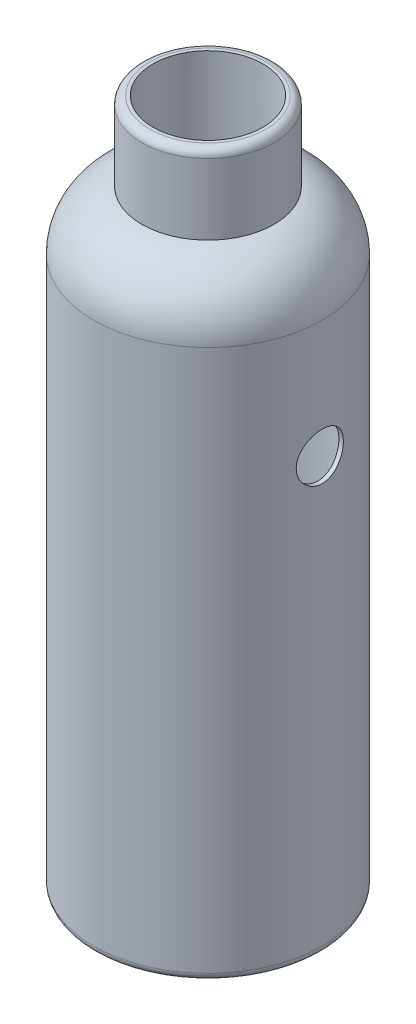
SolidWorks part; units mm, degrees
material "1060 Alloy"
ref_plane "Front Plane" through (0, 0, 0) normal (0, 0, 1) x (1, 0, 0)
ref_plane "Top Plane" through (0, 0, 0) normal (0, 1, 0) x (1, 0, 0)
ref_plane "Right Plane" through (0, 0, 0) normal (1, 0, 0) x (0, 0, -1)
sketch "Sketch1" plane through (0, 0, 0) normal (0, 1, 0) x (1, 0, 0)
  circle A0 centre (0, 0) radius 36.9633
  dimension "D1" = 73.9267
extrude "Boss-Extrude1" add sketch "Sketch1" along normal blind 171.45
fillet "Fillet1" radius 2.54 1 edges at (0, 0, 36.9633)
ref_plane "Plane1" through (0, 196.85, 0) normal (0, 1, 0) x (1, 0, 0)
sketch "Sketch2" plane through (0, 196.85, 0) normal (0, 1, 0) x (1, 0, 0)
  circle A0 centre (0, 0) radius 20.6883
  dimension "D1" = 41.3766
sketch "Sketch10" plane through (0, 171.45, 0) normal (0, 1, 0) x (1, 0, 0)
  circle A0 centre (0, 0) radius 36.9633
  dimension "D1" = 73.9267
extrude "Boss-Extrude2" add sketch "Sketch10" along normal blind 25.4
fillet "Fillet2" radius 19.05 1 edges at (0, 196.85, 36.9633)
sketch "Sketch11" plane through (0, 196.85, 0) normal (0, 1, 0) x (1, 0, 0)
  circle A0 centre (0, 0) radius 21.3678
  dimension "D1" = 42.7355
extrude "Boss-Extrude3" add sketch "Sketch11" along normal blind 25.4
fillet "Fillet3" radius 2.54 1 edges at (0, 222.25, 21.3678)
sketch "Sketch12" plane through (0, 222.25, 0) normal (0, 1, 0) x (1, 0, 0)
  circle A0 centre (0, 0) radius 17.78
  dimension "D1" = 35.56
extrude "Cut-Extrude1" cut sketch "Sketch12" against normal blind 221.742
sketch "Sketch13" plane through (0, 0.508, 0) normal (0, 1, 0) x (1, 0, 0)
  circle A0 centre (0, 0) radius 35.56
  dimension "D1" = 71.12
extrude "Cut-Extrude2" cut sketch "Sketch13" along normal blind 171.45
sketch "Sketch14" plane through (0, 0, 0) normal (0, 0, 1) x (1, 0, 0)
  line L5 (35.56, 171.958) -> (0, 171.958)
  line L6 (-35.56, 171.958) -> (35.56, 171.958) construction
  line L7 (0, 171.958) -> (0, 196.85)
  line L8 (20.6883, 196.85) -> (-20.6883, 196.85) construction
  line L9 (35.56, 171.958) -> (35.56, 177.8)
  line L10 (16.51, 196.85) -> (0, 196.85)
  arc A1 (35.56, 177.8) -> (16.51, 196.85) centre (16.51, 177.8) ccw
  dimension "D1" = 19.05
revolve "Cut-Revolve1" cut sketch "Sketch14" angle 360 about L7
sketch "Sketch15" plane through (0, 0, 0) normal (1, 0, 0) x (0, 0, -1)
  line L0 (36.9634, 177.8) -> (-36.9634, 177.8) construction
  line L1 (0, 177.8) -> (0, 85.8043) construction
  circle A0 centre (0, 139.7) radius 7.62
  dimension "D1" = 15.24
  dimension "D2" = 38.1
extrude "Cut-Extrude3" cut sketch "Sketch15" against normal blind 2.54 and the other way through all
